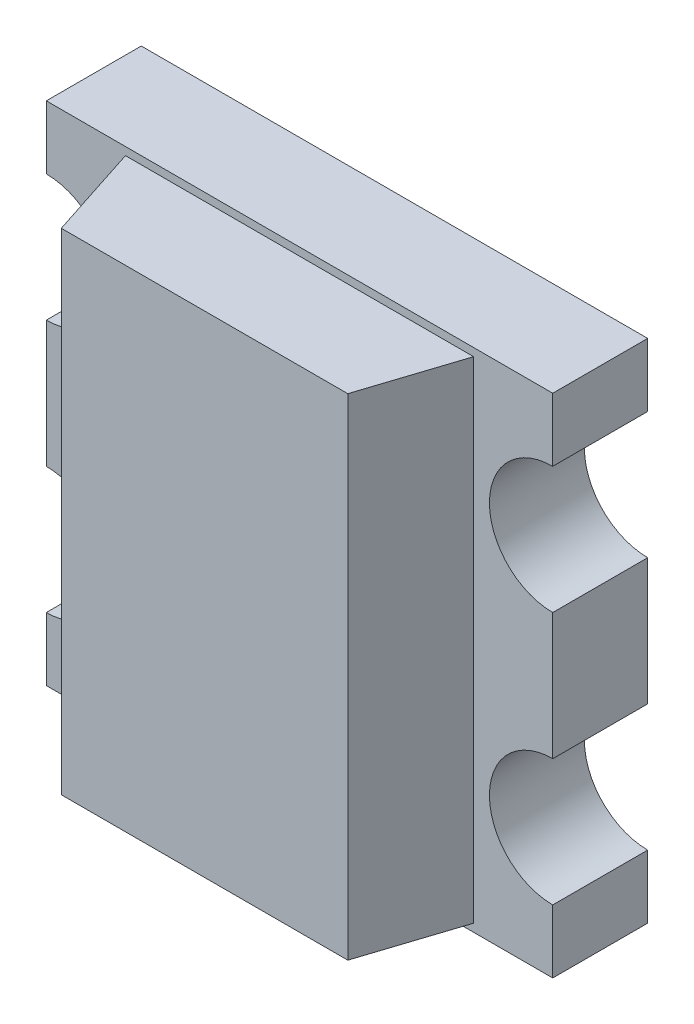
SolidWorks part; units mm, degrees
ref_plane "Front Plane" through (0, 0, 0) normal (0, 0, 1) x (1, 0, 0)
ref_plane "Top Plane" through (0, 0, 0) normal (0, 1, 0) x (1, 0, 0)
ref_plane "Right Plane" through (0, 0, 0) normal (1, 0, 0) x (0, 0, -1)
sketch "Sketch2" plane through (0, 0, 0) normal (0, 0, 1) x (1, 0, 0)
  line L0 (0, 0.8) -> (0, 0) construction
  line L1 (0, 0) -> (0.8, 0) construction
  line L2 (-0.8, 0.8) -> (0.8, 0.8)
  line L3 (0.8, 0.8) -> (0.8, 0.6)
  line L4 (0.8, -0.2) -> (0.8, 0.2)
  line L5 (0.8, -0.8) -> (0.8, -0.6)
  line L6 (-0.8, -0.8) -> (0.8, -0.8)
  line L7 (-0.8, -0.8) -> (-0.8, -0.6)
  line L8 (-0.8, -0.2) -> (-0.8, 0.2)
  line L9 (-0.8, 0.8) -> (-0.8, 0.6)
  arc A0 (0.8, 0.6) -> (0.8, 0.2) centre (0.8, 0.4) ccw
  arc A1 (0.8, -0.6) -> (0.8, -0.2) centre (0.8, -0.4) cw
  arc A2 (-0.8, -0.6) -> (-0.8, -0.2) centre (-0.8, -0.4) ccw
  arc A3 (-0.8, 0.6) -> (-0.8, 0.2) centre (-0.8, 0.4) cw
  point P8 (0, 0)
  point P9 (0, 0)
  point P10 (0.8175, 0.5582)
  point P11 (0, 0)
  point P12 (0.8349, 0.2665)
  point P13 (0, 0)
  point P14 (0, 0)
  point P21 (0, -0.8)
  dimension "D3" = 0.2
  dimension "D1" = 1.6
  dimension "D2" = 1.6
  dimension "D4" = 0.2
extrude "Boss-Extrude1" add sketch "Sketch2" along normal blind 0.3
sketch "Sketch3" plane through (0, 0, 0) normal (0, 1, 0) x (1, 0, 0)
  line L0 (0.55, -0.3) -> (0.4525, -0.6)
  line L1 (0.8, -0.3) -> (-0.8, -0.3) construction
  line L2 (0.4525, -0.6) -> (-0.4525, -0.6)
  line L3 (0, -0.6) -> (0, -0.3) construction
  line L4 (-0.55, -0.3) -> (0.55, -0.3)
  line L5 (-0.55, -0.3) -> (-0.4525, -0.6)
  line L6 (0.8, 0) -> (-0.8, 0) construction
  dimension "D1" = 0.6
  dimension "D2" = 72
  dimension "D3" = 1.1
extrude "Boss-Extrude2" add sketch "Sketch3" along normal mid plane 1.55
